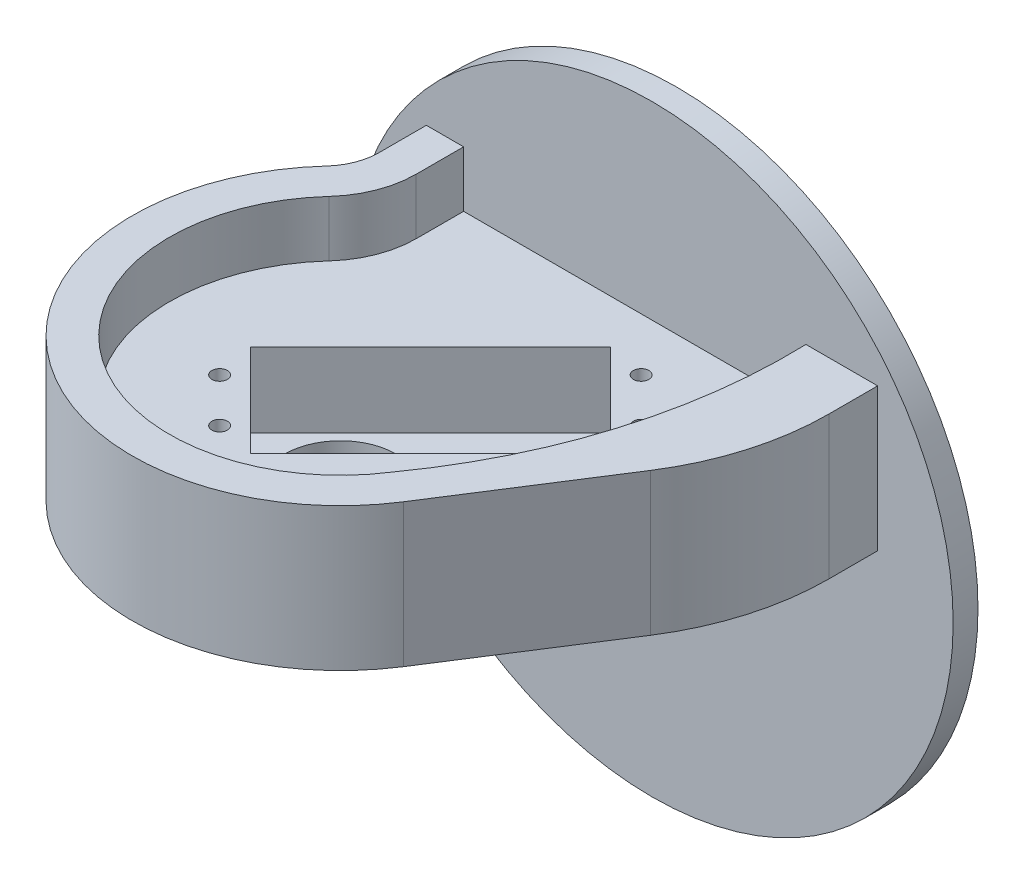
SolidWorks part; units mm, degrees
ref_plane "Front Plane" through (0, 0, 0) normal (1, 0, 0) x (0, 1, 0)
ref_plane "Top Plane" through (0, 0, 0) normal (0, 0, 1) x (0, 1, 0)
ref_plane "Right Plane" through (0, 0, 0) normal (0, 1, 0) x (-1, 0, 0)
sketch "Sketch1" plane through (0, 0, 0) normal (0, 0, 1) x (0, 1, 0)
  line L0 (0, 7.25) -> (0, -7.25) construction
  circle A0 centre (0, 0) radius 48.5
  circle A1 centre (0, 7.25) radius 1.5
  circle A2 centre (0, -7.25) radius 1.5
  point P6 (0, 0)
  dimension "D1" = 97
  dimension "D3" = 3
  dimension "D2" = 14.5
extrude "Boss-Extrude1" add sketch "Sketch1" along normal blind 4
sketch "Sketch2" plane through (0, 0, 4) normal (0, 0, 1) x (1, 0, 0)
  circle A0 centre (0, 0) radius 3.75
  dimension "D1" = 7.5
extrude "Cut-Extrude1" cut sketch "Sketch2" against normal blind 1.5
sketch "Sketch3" plane through (0, 0, 0) normal (0, 1, 0) x (-1, 0, 0)
  line L0 (-30.34, 4) -> (-30.34, 11.86)
  line L1 (-24.7927, 30.8361) -> (-9.2781, 55.1041)
  line L2 (-48.5, 0) -> (48.5, 0) construction
  line L3 (30.34, 4) -> (-30.34, 4)
  line L4 (48.5, 4) -> (-48.5, 4) construction
  line L5 (30.34, 4) -> (30.34, 11.64)
  arc A0 (30.34, 11.64) -> (34.2527, 21.7431) centre (45.34, 11.64) cw
  arc A1 (34.2527, 21.7431) -> (-9.2781, 55.1041) centre (13.91, 40.28) ccw
  arc A2 (-30.34, 11.86) -> (-24.7927, 30.8361) centre (4.89, 11.86) cw
  circle A3 centre (13.91, 40.28) radius 9
  point P6 (0, 4)
  dimension "D3" = 15
  dimension "D5" = 35.23
  dimension "D6" = 18
  dimension "D1" = 60.68
  dimension "D2" = 7.64
  dimension "D4" = 7.86
  dimension "D7" = 13.91
  dimension "D8" = 40.28
extrude "Boss-Extrude2" add sketch "Sketch3" along normal blind 14 from offset 4
sketch "Sketch4" plane through (0, 0, 0) normal (0, 1, 0) x (-1, 0, 0)
  line L0 (-0.41, 11.1108) -> (28.5814, 40.1021)
  line L1 (-0.41, 11.1108) -> (-15.2592, 25.96)
  line L2 (28.5814, 40.1021) -> (13.7321, 54.9514)
  line L3 (-15.2592, 25.96) -> (13.7321, 54.9514)
  line L4 (48.5, 4) -> (-48.5, 4) construction
  line L5 (-0.7636, 40.4557) -> (14.0857, 25.6064) construction
  line L6 (6.6611, 33.0311) -> (21.1568, 47.5268) construction
  line L8 (21.1568, 47.5268) -> (23.6316, 50.0016) construction
  line L9 (27.1672, 46.4661) -> (20.0961, 53.5372) construction
  circle A1 centre (20.0961, 53.5372) radius 1.25
  circle A2 centre (27.1672, 46.4661) radius 1.25
  circle A3 centre (-6.774, 12.525) radius 1.25
  circle A4 centre (-13.845, 19.596) radius 1.25
  point P17 (13.91, 40.28)
  point P20 (23.6316, 50.0016)
  point P22 (17.2248, 56.4084)
  dimension "D7" = 2.5
  dimension "D1" = 0.41
  dimension "D2" = 21
  dimension "D3" = 41
  dimension "D4" = 10
  dimension "D5" = 45
  dimension "D6" = 3.5
extrude "Cut-Extrude2" cut sketch "Sketch4" along normal through all from offset 6
sketch "Sketch5" plane through (0, 18, 0) normal (0, 1, 0) x (-1, 0, 0)
  line L0 (33.34, 4) -> (33.34, 11.64) construction
  line L1 (-11.8057, 56.7201) -> (-27.3203, 32.452) construction
  line L2 (-33.34, 11.86) -> (-33.34, 4) construction
  line L3 (36.34, 4) -> (36.34, 11.64)
  line L4 (-30.34, 4) -> (30.34, 4)
  line L5 (30.34, 4) -> (30.34, 11.64)
  line L6 (-9.2781, 55.1041) -> (-24.7927, 30.8361)
  line L7 (-30.34, 11.86) -> (-30.34, 4)
  line L9 (30.34, 4) -> (30.34, 11.64)
  line L10 (-9.2781, 55.1041) -> (-24.7927, 30.8361) construction
  line L11 (-30.34, 11.86) -> (-30.34, 4) construction
  line L12 (-14.3333, 58.336) -> (-29.8479, 34.0679)
  line L13 (-36.34, 11.86) -> (-36.34, 4)
  line L14 (48.5, 4) -> (-48.5, 4) construction
  line L15 (-36.34, 4) -> (-33.34, 4)
  line L16 (-33.34, 4) -> (-30.34, 4)
  line L17 (30.34, 4) -> (33.34, 4)
  line L18 (33.34, 4) -> (36.34, 4)
  line L19 (-30.34, 4) -> (-24.79, 4)
  arc A0 (36.4702, 19.7225) -> (33.34, 11.64) centre (45.34, 11.64) ccw construction
  arc A1 (36.4702, 19.7225) -> (-11.8057, 56.7201) centre (13.91, 40.28) ccw construction
  arc A2 (-27.3203, 32.452) -> (-33.34, 11.86) centre (4.89, 11.86) ccw construction
  arc A3 (34.2527, 21.7431) -> (30.34, 11.64) centre (45.34, 11.64) ccw
  arc A4 (34.2527, 21.7431) -> (-9.2781, 55.1041) centre (13.91, 40.28) ccw
  arc A5 (-24.7927, 30.8361) -> (-30.34, 11.86) centre (4.89, 11.86) ccw
  arc A6 (34.2527, 21.7431) -> (30.34, 11.64) centre (45.34, 11.64) ccw
  arc A7 (34.2527, 21.7431) -> (-9.2781, 55.1041) centre (13.91, 40.28) ccw
  arc A8 (-24.7927, 30.8361) -> (-30.34, 11.86) centre (4.89, 11.86) ccw construction
  arc A9 (38.6876, 17.7018) -> (36.34, 11.64) centre (45.34, 11.64) ccw
  arc A10 (38.6876, 17.7018) -> (-14.3333, 58.336) centre (13.91, 40.28) ccw
  arc A11 (-29.8479, 34.0679) -> (-36.34, 11.86) centre (4.89, 11.86) ccw
  arc A12 (-9.2781, 55.1041) -> (-24.79, 4) centre (58.1652, 6.7265) ccw
  dimension "D5" = 83
  dimension "D4" = 5.55
  dimension "D1" = 0
  dimension "D2" = 3
  dimension "D3" = 3
extrude "Boss-Extrude3" add sketch "Sketch5" along normal blind 9 and the other way up to surface other way up to face at (-2.2919, 4, 23.3781)
